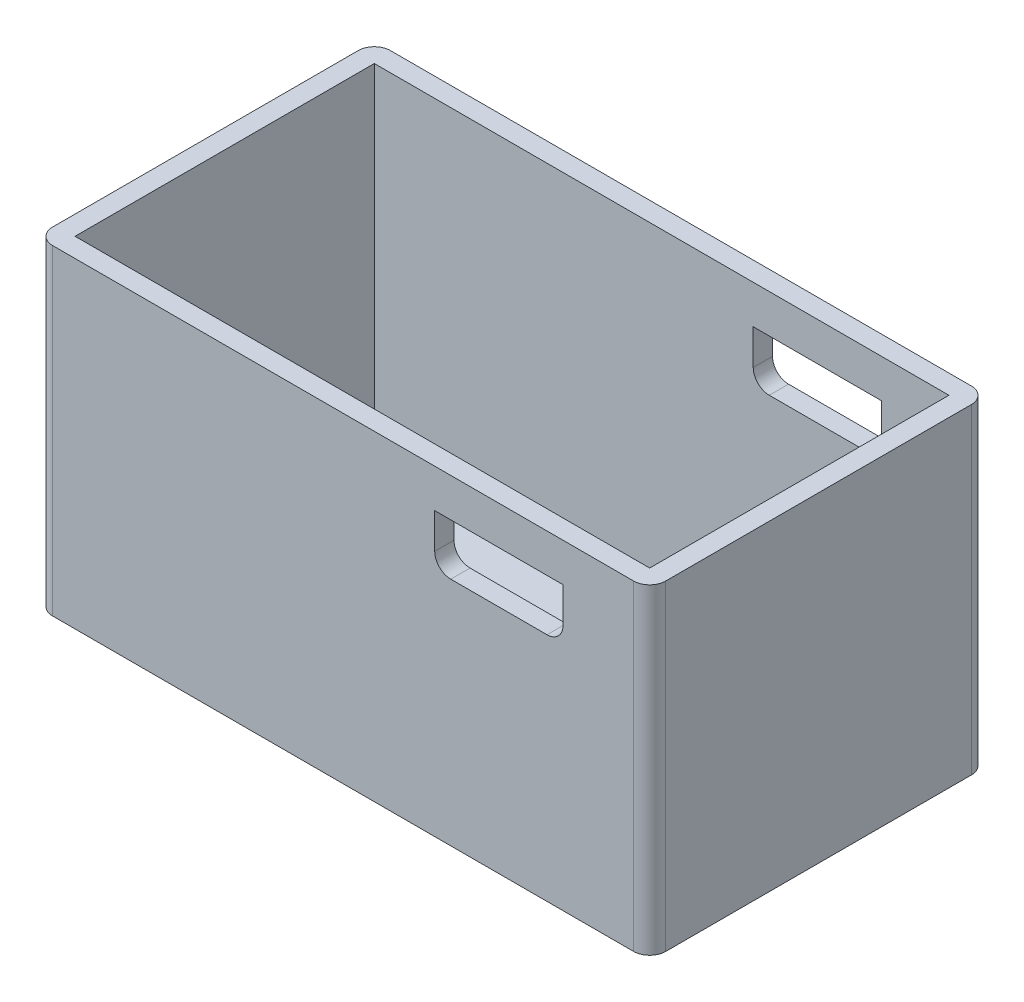
SolidWorks part; units mm, degrees
ref_plane "Front Plane" through (0, 0, 0) normal (0, 0, 1) x (1, 0, 0)
ref_plane "Top Plane" through (0, 0, 0) normal (0, 1, 0) x (1, 0, 0)
ref_plane "Right Plane" through (0, 0, 0) normal (1, 0, 0) x (0, 0, -1)
sketch "Sketch1" plane through (0, 0, 0) normal (0, 1, 0) x (1, 0, 0)
  line L1 (-12.135, 6.685) -> (12.135, 6.685)
  line L2 (-12.135, 6.685) -> (-12.135, -6.685)
  line L3 (-12.135, -6.685) -> (12.135, -6.685)
  line L4 (12.135, 6.685) -> (12.135, -6.685)
  line L5 (-12.135, 6.685) -> (12.135, -6.685) construction
  line L6 (-12.135, -6.685) -> (12.135, 6.685) construction
  point P0 (0, 0)
  dimension "D1" = 24.27
  dimension "D2" = 13.37
extrude "Boss-Extrude1" add sketch "Sketch1" along normal blind 12.7
shell "Shell1" thickness 0.762
fillet "Fillet1" radius 0.635 4 edges at (-12.135, 6.35, -6.685) (-12.135, 6.35, 6.685) (12.135, 6.35, -6.685) (12.135, 6.35, 6.685)
sketch "Sketch2" plane through (0, 0, 6.685) normal (0, 0, 1) x (1, 0, 0)
  line L0 (-11.5, 12.7) -> (11.5, 12.7) construction
  line L1 (3.626, 11.176) -> (8.706, 11.176)
  line L2 (3.626, 11.176) -> (3.626, 9.144)
  line L3 (3.626, 9.144) -> (8.706, 9.144)
  line L4 (8.706, 11.176) -> (8.706, 9.144)
  line L5 (3.626, 11.176) -> (8.706, 9.144) construction
  line L6 (3.626, 9.144) -> (8.706, 11.176) construction
  line L7 (11.5, 0) -> (11.5, 12.7) construction
  point P0 (6.166, 10.16)
  dimension "D1" = 5.08
  dimension "D2" = 2.032
  dimension "D3" = 1.524
  dimension "D4" = 2.794
extrude "Cut-Extrude1" cut sketch "Sketch2" against normal through all
fillet "Fillet2" radius 0.635 4 edges at (3.626, 9.144, -6.304) (8.706, 9.144, -6.304) (8.706, 9.144, 6.304) (3.626, 9.144, 6.304)
